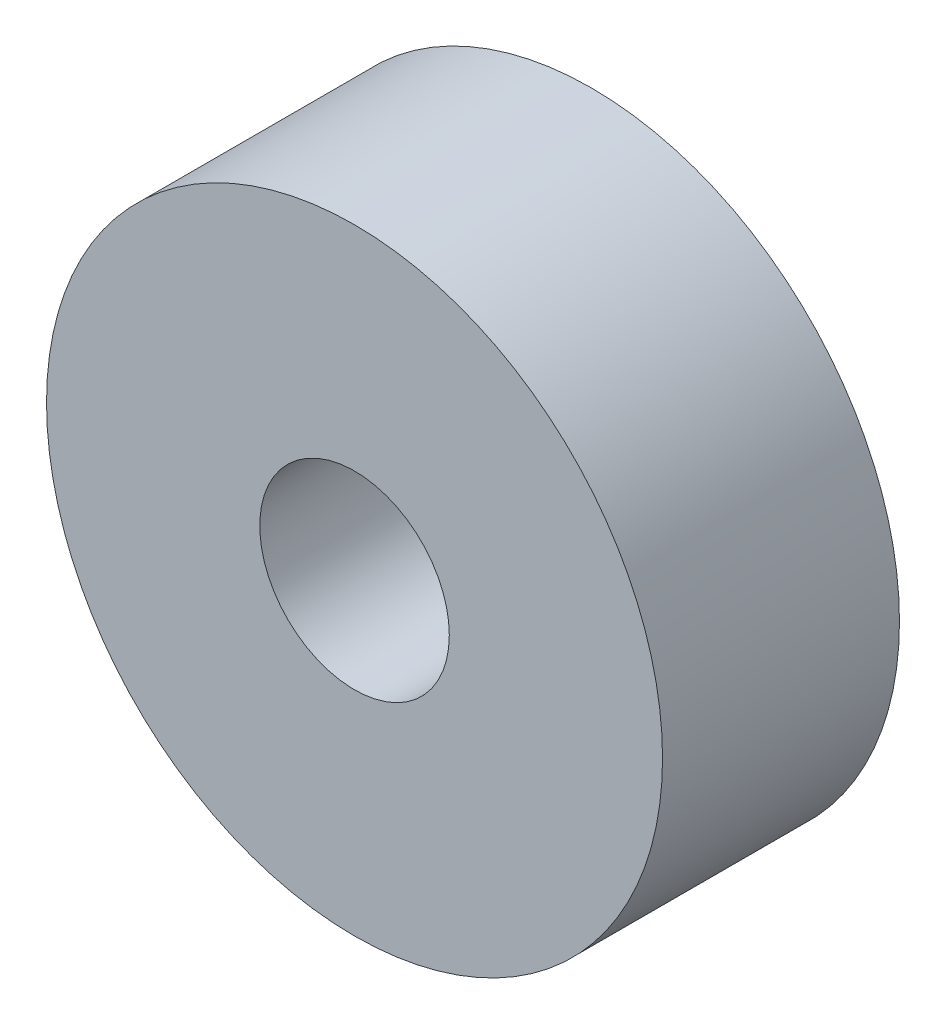
SolidWorks part; units mm, degrees
ref_plane "前视基准面" through (0, 0, 0) normal (0, 0, 1) x (1, 0, 0)
ref_plane "上视基准面" through (0, 0, 0) normal (0, 1, 0) x (1, 0, 0)
ref_plane "右视基准面" through (0, 0, 0) normal (1, 0, 0) x (0, 0, -1)
sketch "草图1" plane through (0, 0, 0) normal (0, 0, 1) x (1, 0, 0)
  circle A0 centre (0, 0) radius 2
  circle A1 centre (0, 0) radius 6.5
  dimension "D1" = 4
  dimension "D2" = 13
extrude "凸台-拉伸1" add sketch "草图1" along normal blind 5
